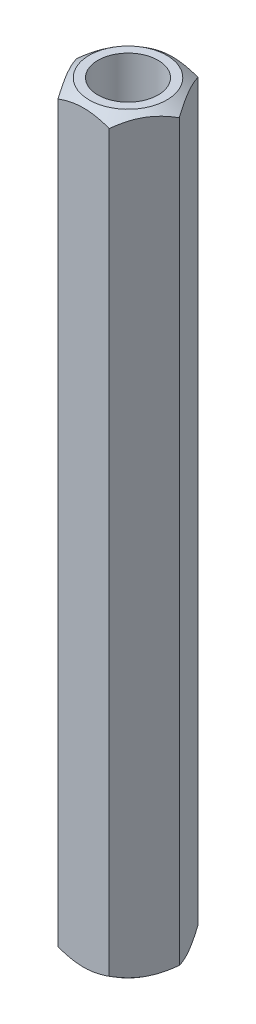
SolidWorks part; units mm, degrees
ref_plane "前视基准面" through (0, 0, 0) normal (0, 0, 1) x (1, 0, 0)
ref_plane "上视基准面" through (0, 0, 0) normal (0, 1, 0) x (1, 0, 0)
ref_plane "右视基准面" through (0, 0, 0) normal (1, 0, 0) x (0, 0, -1)
sketch "草图1" plane through (0, 0, 0) normal (0, 1, 0) x (1, 0, 0)
  line L0 (-7.4699, 0) -> (7.7349, 0) construction
  line L2 (1.7032, -2.95) -> (3.4064, 0)
  line L3 (3.4064, 0) -> (1.7032, 2.95)
  line L4 (1.7032, 2.95) -> (-1.7032, 2.95)
  line L5 (-1.7032, 2.95) -> (-3.4064, 0)
  line L6 (-3.4064, 0) -> (-1.7032, -2.95)
  line L7 (-1.7032, -2.95) -> (1.7032, -2.95)
  circle A0 centre (0, 0) radius 2.95 construction
  circle A1 centre (0, 0) radius 2
  dimension "D1" = 5.9
  dimension "D2" = 4
extrude "凸台-拉伸1" add sketch "草图1" along normal blind 50
sketch "草图3" plane through (0, 0, 0) normal (0, 0, 1) x (1, 0, 0)
  line L0 (-8.6372, 0) -> (9.5852, 0) construction
  line L1 (0, 59.1821) -> (0, -22.7239) construction
  line L2 (6.9786, 3.2) -> (1.2, -1)
  line L3 (1.2, -1) -> (6.9786, -1)
  line L4 (6.9786, -1) -> (6.9786, 3.2)
  dimension "D1" = 1.2
  dimension "D2" = 1
  dimension "D3" = 4.2
revolve "切除-旋转1" cut sketch "草图3" angle 360 about L1
ref_plane "基准面1" through (0, 25, 0) normal (0, 1, 0) x (1, 0, 0)
mirror "镜向1" about plane through (0, 25, 0) normal (0, 1, 0) of "切除-旋转1"
